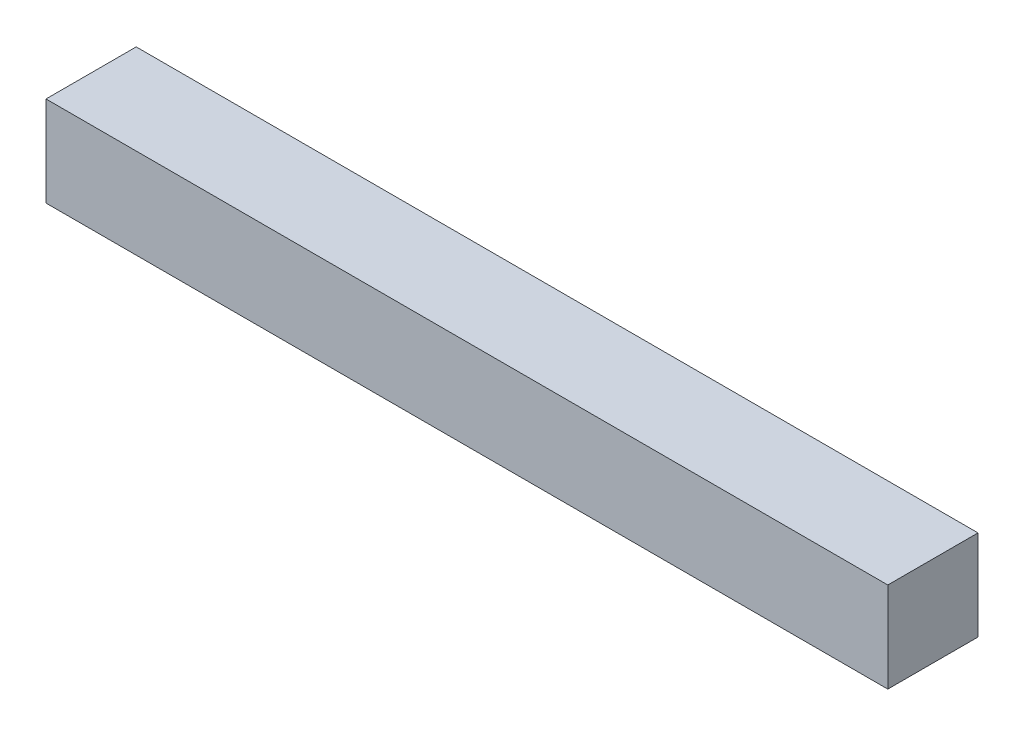
SolidWorks part; units mm, degrees
ref_plane "Front Plane" through (0, 0, 0) normal (0, 0, 1) x (1, 0, 0)
ref_plane "Top Plane" through (0, 0, 0) normal (0, 1, 0) x (1, 0, 0)
ref_plane "Right Plane" through (0, 0, 0) normal (1, 0, 0) x (0, 0, -1)
other "Configuration Table"
sketch "Sketch1" plane through (0, 0, 0) normal (0, 0, 1) x (1, 0, 0)
  line L1 (-70, 245) -> (70, 245)
  line L2 (-70, 245) -> (-70, 260)
  line L3 (-70, 260) -> (70, 260)
  line L4 (70, 245) -> (70, 260)
extrude "KAPYAG_on_cekme_dudagi_1" add sketch "Sketch1" against normal blind 15 from offset 5 separate body
